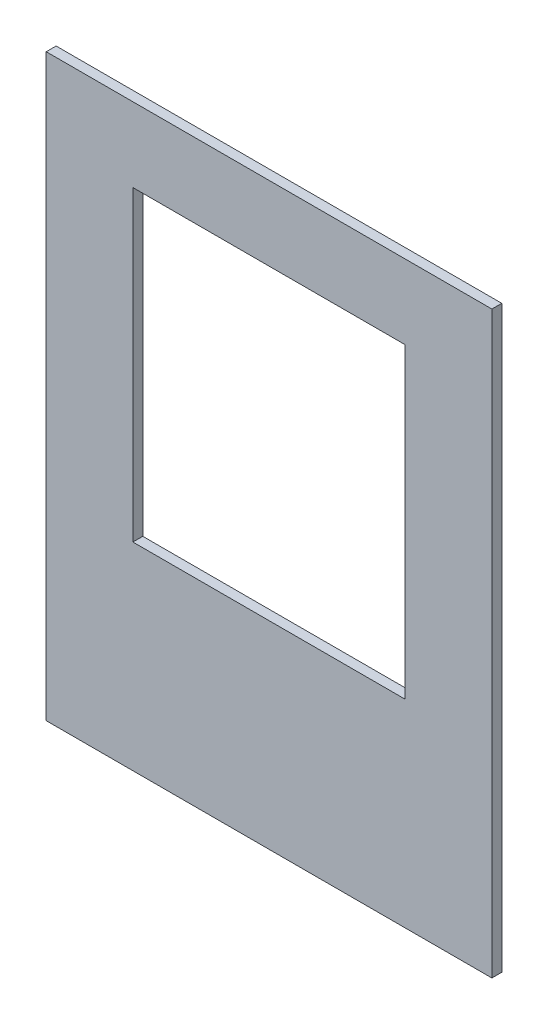
SolidWorks part; units mm, degrees
ref_plane "Front Plane" through (0, 0, 0) normal (0, 0, 1) x (1, 0, 0)
ref_plane "Top Plane" through (0, 0, 0) normal (0, 1, 0) x (1, 0, 0)
ref_plane "Right Plane" through (0, 0, 0) normal (1, 0, 0) x (0, 0, -1)
sketch "Sketch1" plane through (0, 0, 0) normal (0, 0, 1) x (1, 0, 0)
  line L0 (-180, 184) -> (180, 184)
  line L1 (-110, -124) -> (110, -124)
  line L2 (-110, -124) -> (-110, 124)
  line L3 (-110, 124) -> (110, 124)
  line L4 (110, -124) -> (110, 124)
  line L5 (-110, -124) -> (110, 124) construction
  line L6 (-110, 124) -> (110, -124) construction
  line L7 (180, -194) -> (180, 184)
  line L8 (-180, -194) -> (180, -194)
  line L9 (-180, -194) -> (-180, 184)
  line L11 (-180, -194) -> (180, -194)
  line L12 (-180, -194) -> (-180, -284)
  line L13 (-180, -284) -> (180, -284)
  line L14 (180, -194) -> (180, -284)
  point P0 (0, 0)
  dimension "D1" = 248
  dimension "D2" = 220
  dimension "D4" = 90
  dimension "D3" = 60
  dimension "D5" = 70
  dimension "D6" = 70
  dimension "D7" = 70
extrude "Boss-Extrude1" add sketch "Sketch1" along normal blind 8 contours L14 L8 L12 L13 | L9 L8 L7 L0 L4 L1 L2 L3
